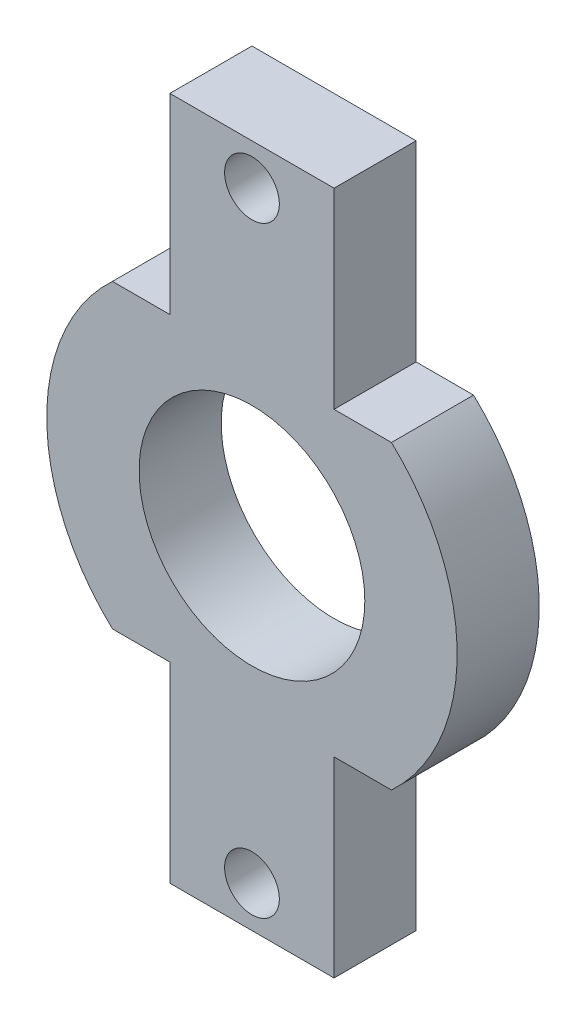
SolidWorks part; units mm, degrees
material "Pine"
ref_plane "Front Plane" through (0, 0, 0) normal (0, 0, 1) x (1, 0, 0)
ref_plane "Top Plane" through (0, 0, 0) normal (0, 1, 0) x (1, 0, 0)
ref_plane "Right Plane" through (0, 0, 0) normal (1, 0, 0) x (0, 0, -1)
sketch "Sketch1" plane through (0, 0, 0) normal (0, 0, 1) x (1, 0, 0)
  line L0 (0, -8.25) -> (0, 99.907) construction
  line L1 (-8.25, 0) -> (22.5, 0) construction
  line L2 (6, -25) -> (6, -11)
  line L3 (-6, -25) -> (-6, -11)
  line L4 (-10.198, 11) -> (-6, 11)
  line L5 (10.198, -11) -> (6, -11)
  line L6 (6, 11) -> (10.198, 11)
  line L7 (-6, -11) -> (-10.198, -11)
  line L8 (6, -8.25) -> (6, 99.907) construction
  line L9 (-6, -8.25) -> (-6, 99.907) construction
  line L11 (-6, -25) -> (6, -25)
  line L13 (-6, 25) -> (6, 25)
  line L16 (-6, 11) -> (-6, 25)
  line L17 (6, 11) -> (6, 25)
  circle A0 centre (0, 0) radius 8.25
  arc A1 (10.198, -11) -> (10.198, 11) centre (0, 0) ccw
  arc A5 (-10.198, 11) -> (-10.198, -11) centre (0, 0) ccw
  point P5 (-9.5, -20)
  point P7 (22.5, -20)
  point P12 (-9.5, 20)
  point P13 (22.5, 20)
  dimension "D5" = 11
  dimension "D6" = 16.5
  dimension "D9" = 30
  dimension "D3" = 50
  dimension "D4" = 25
  dimension "D7" = 11
  dimension "D1" = 6
  dimension "D2" = 6
extrude "Boss-Extrude1" add sketch "Sketch1" along normal blind 6
sketch "Sketch3" plane through (0, 0, 0) normal (0, 0, -1) x (-1, 0, 0)
  line L0 (6, -25) -> (-6, -25) construction
  line L1 (-6, 25) -> (6, 25) construction
  circle A0 centre (0, 22) radius 2
  circle A1 centre (0, -22) radius 2
  point P4 (0, -25)
  point P8 (0, 25)
  dimension "D3" = 4
  dimension "D1" = 3
  dimension "D2" = 3
extrude "Cut-Extrude1" cut sketch "Sketch3" against normal through all
